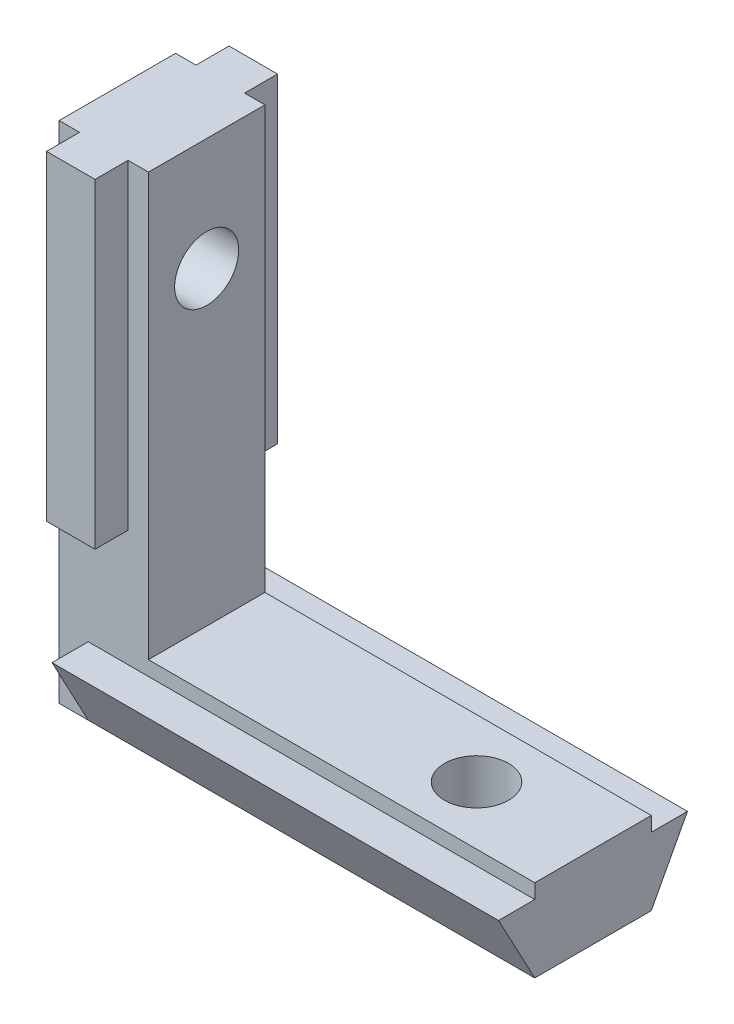
SolidWorks part; units mm, degrees
material "Zinc AC41A Alloy, As Cast"
ref_plane "Front Plane" through (0, 0, 0) normal (0, 0, 1) x (1, 0, 0)
ref_plane "Top Plane" through (0, 0, 0) normal (0, 1, 0) x (1, 0, 0)
ref_plane "Right Plane" through (0, 0, 0) normal (1, 0, 0) x (0, 0, -1)
sketch "Sketch1" plane through (0, 0, 0) normal (0, 0, 1) x (1, 0, 0)
  line L0 (0, 26) -> (0, 0)
  line L1 (0, 0) -> (25.5, 0)
  line L2 (25.5, 0) -> (25.5, 5)
  line L3 (25.5, 5) -> (8, 5)
  line L4 (5, 8) -> (5, 26)
  line L5 (5, 26) -> (0, 26)
  arc A0 (8, 5) -> (5, 8) centre (8, 8) cw
  dimension "D5" = 3
  dimension "D1" = 26
  dimension "D2" = 25.5
  dimension "D3" = 5
  dimension "D4" = 5
extrude "Boss-Extrude1" add sketch "Sketch1" along normal mid plane 6
sketch "Sketch2" plane through (25.5, 0, 0) normal (1, 0, 0) x (0, 0, -1)
  line L0 (-3, 0) -> (-5, 3.75)
  line L1 (-5, 3.75) -> (5, 3.75)
  line L2 (0, 3.75) -> (0, 0) construction
  line L3 (-3, 0) -> (3, 0)
  line L4 (3, 0) -> (5, 3.75)
  line L5 (-3, 5) -> (3, 5) construction
  dimension "D1" = 10
  dimension "D2" = 1.25
extrude "Boss-Extrude2" add sketch "Sketch2" against normal blind 24
sketch "Sketch3" plane through (0, 26, 0) normal (0, 1, 0) x (1, 0, 0)
  line L0 (1.5, 0) -> (0, 0) construction
  line L1 (1.5, 5.2) -> (2.8, 5.2)
  line L2 (1.5, 5.2) -> (1.5, -5.2)
  line L3 (1.5, -5.2) -> (2.8, -5.2)
  line L4 (2.8, 5.2) -> (2.8, -5.2)
  line L5 (0, -3) -> (0, 3) construction
  line L6 (1.5, 5) -> (1.5, 3) construction
  dimension "D1" = 2.8
  dimension "D2" = 10.4
extrude "Boss-Extrude3" add sketch "Sketch3" against normal blind 16.5
hole_wizard "M4x0.7 Tapped Hole1" positions "Sketch5" profile "Sketch4" tap size "M4x0.7" standard "ANSI Metric" end condition through all
sketch "Sketch5" plane through (0, 5, 0) normal (0, 1, 0) x (1, 0, 0)
  line L0 (18.5, 0) -> (25.5, 0) construction
  line L1 (25.5, -3) -> (25.5, 3) construction
  point P0 (18.5, 0)
  dimension "D1" = 7
sketch "Sketch4" plane through (18.5, 5, 0) normal (1, 0, 0) x (0, 0, 1)
  line L0 (0, 0) -> (0, 5)
  line L1 (0, 5) -> (1.65, 5)
  line L2 (1.65, 5) -> (1.65, 0)
  line L5 (1.65, 0) -> (0, 0)
  line L11 (0, -6.35) -> (0, 107.95) construction
  dimension "Thread Major Dia." = 3.3
  dimension "Thru Tap Drill Depth" = 5
hole_wizard "M4x0.7 Tapped Hole2" positions "Sketch7" profile "Sketch6" tap size "M4x0.7" standard "ANSI Metric" end condition through all
sketch "Sketch7" plane through (5, 0, 0) normal (1, 0, 0) x (0, 0, -1)
  line L0 (0, 26) -> (0, 20.2) construction
  line L1 (-3, 26) -> (3, 26) construction
  point P0 (0, 20.2)
  dimension "D1" = 5.8
sketch "Sketch6" plane through (5, 20.2, 0) normal (0, 1, 0) x (0, 0, -1)
  line L0 (0, 0) -> (0, 5)
  line L1 (0, 5) -> (1.65, 5)
  line L2 (1.65, 5) -> (1.65, 0)
  line L5 (1.65, 0) -> (0, 0)
  line L11 (0, -6.35) -> (0, 107.95) construction
  dimension "Thread Major Dia." = 3.3
  dimension "Thru Tap Drill Depth" = 5
sketch "Sketch9" plane through (0, 0, -3) normal (0, 0, -1) x (-1, 0, 0)
  line L1 (-5, 8) -> (-8, 8)
  line L2 (-5, 8) -> (-5, 5)
  line L3 (-5, 5) -> (-8, 5)
  line L4 (-8, 8) -> (-8, 5)
extrude "Cut-Extrude1" cut sketch "Sketch9" against normal through all
other "Move Face1" face at (15.25, 5, 0) parameters "D1"=0.75
other "Move Face2" face at (5, 20.2, -1.65) parameters "D1"=0.4
other "Move Face3" face at (2.8, 17.75, 4.1) face at (2.8, 17.75, -4.1) parameters "D1"=0.75
other "Move Face4" face at (1.5, 17.75, 4.1) face at (1.5, 17.75, -4.1) parameters "D1"=0.45
other "Move Face5" face at (2.3, 17.75, 5.2) face at (2.3, 17.75, -5.2) parameters "D1"=0.5
other "Move Face6" face at (25.5, 2.9375, 0) parameters "D1"=1
other "Move Face8" face at (13, 3.75, -4) face at (13, 3.75, 4) parameters "D1"=0.25
